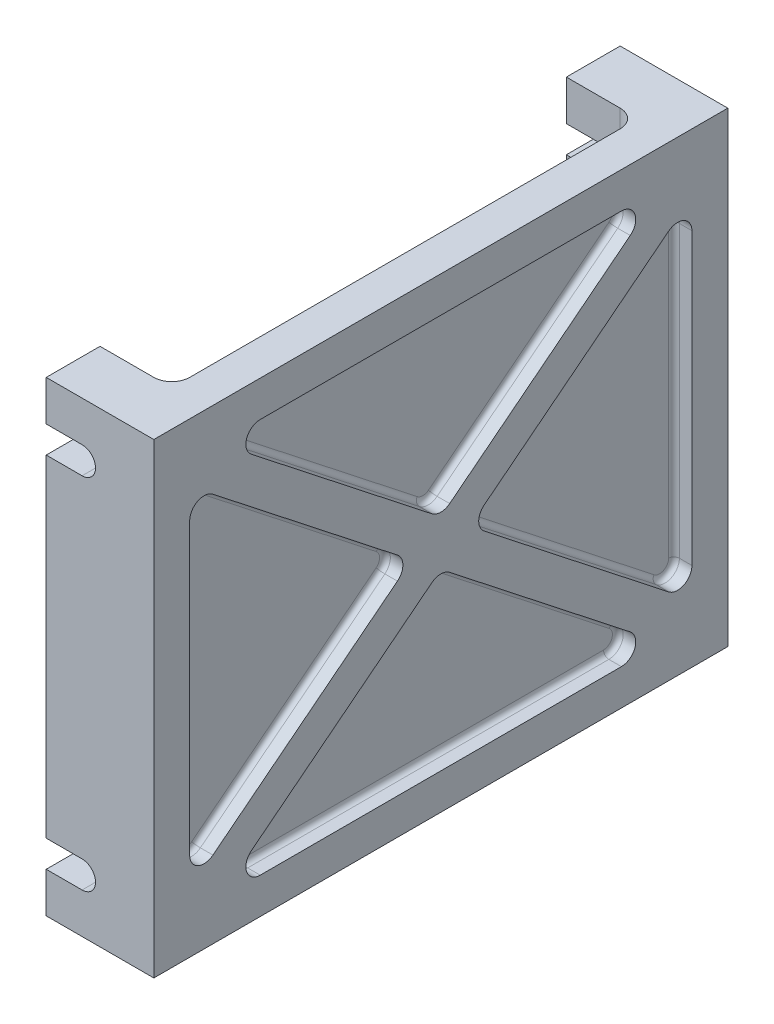
SolidWorks part; units mm, degrees
ref_plane "Front Plane" through (0, 0, 0) normal (0, 0, 1) x (1, 0, 0)
ref_plane "Top Plane" through (0, 0, 0) normal (0, 1, 0) x (1, 0, 0)
ref_plane "Right Plane" through (0, 0, 0) normal (1, 0, 0) x (0, 0, -1)
sketch "Sketch1" plane through (0, 0, 0) normal (1, 0, 0) x (0, 0, -1)
  line L1 (50.8, -41.275) -> (-50.8, -41.275)
  line L2 (50.8, -41.275) -> (50.8, 41.275)
  line L3 (50.8, 41.275) -> (-50.8, 41.275)
  line L4 (-50.8, -41.275) -> (-50.8, 41.275)
  line L5 (50.8, -41.275) -> (-50.8, 41.275) construction
  line L6 (50.8, 41.275) -> (-50.8, -41.275) construction
  point P0 (0, 0)
  dimension "D1" = 101.6
  dimension "D2" = 82.55
extrude "Boss-Extrude1" add sketch "Sketch1" along normal blind 3.175
sketch "Sketch2" plane through (3.175, 0, 0) normal (1, 0, 0) x (0, 0, -1)
  line L0 (50.8, 41.275) -> (-50.8, 41.275) construction
  line L1 (31.967, -34.925) -> (-31.967, -34.925)
  line L2 (44.45, -25.6612) -> (44.45, 25.6612)
  line L3 (31.967, 34.925) -> (-31.967, 34.925)
  line L4 (-44.45, -25.6612) -> (-44.45, 25.6612)
  line L5 (2.5695, -2.0189) -> (-2.5695, 2.0189) construction
  line L6 (2.5695, 2.0189) -> (-2.5695, -2.0189) construction
  line L7 (-50.8, 41.275) -> (-50.8, -41.275) construction
  line L8 (33.5363, -30.3878) -> (1.5693, -5.2708)
  line L9 (-33.5363, 30.3878) -> (-1.5693, 5.2708)
  line L10 (33.5363, 30.3878) -> (1.5693, 5.2708)
  line L11 (40.3407, 27.6585) -> (7.681, 1.9972)
  line L12 (-1.5693, -5.2708) -> (-33.5363, -30.3878)
  line L13 (-7.681, 1.9972) -> (-40.3407, 27.6585)
  line L14 (-7.681, -1.9972) -> (-40.3407, -27.6585)
  line L15 (7.681, -1.9972) -> (40.3407, -27.6585)
  line L17 (50.8, -41.275) -> (-50.8, -41.275)
  line L18 (50.8, -41.275) -> (50.8, 41.275)
  line L19 (50.8, 41.275) -> (-50.8, 41.275)
  line L20 (-50.8, -41.275) -> (-50.8, 41.275)
  line L21 (50.8, -41.275) -> (-50.8, 41.275) construction
  line L22 (50.8, 41.275) -> (-50.8, -41.275) construction
  arc A0 (-1.5693, -5.2708) -> (1.5693, -5.2708) centre (0, -7.268) cw
  arc A1 (7.681, -1.9972) -> (7.681, 1.9972) centre (9.2502, 0) cw
  arc A2 (1.5693, 5.2708) -> (-1.5693, 5.2708) centre (0, 7.268) cw
  arc A3 (-7.681, 1.9972) -> (-7.681, -1.9972) centre (-9.2502, 0) cw
  arc A4 (-40.3407, -27.6585) -> (-44.45, -25.6612) centre (-41.91, -25.6612) cw
  arc A5 (-33.5363, -30.3878) -> (-31.967, -34.925) centre (-31.967, -32.385) ccw
  arc A6 (33.5363, -30.3878) -> (31.967, -34.925) centre (31.967, -32.385) cw
  arc A7 (40.3407, -27.6585) -> (44.45, -25.6612) centre (41.91, -25.6612) ccw
  arc A8 (40.3407, 27.6585) -> (44.45, 25.6612) centre (41.91, 25.6612) cw
  arc A9 (33.5363, 30.3878) -> (31.967, 34.925) centre (31.967, 32.385) ccw
  arc A10 (-33.5363, 30.3878) -> (-31.967, 34.925) centre (-31.967, 32.385) cw
  arc A11 (-40.3407, 27.6585) -> (-44.45, 25.6612) centre (-41.91, 25.6612) ccw
  point P0 (0, 0)
  point P30 (-5.139, 0)
  point P47 (0, 0)
  line M9 (-50.8, 41.275) -> (-50.8, -41.275)
  line M10 (-50.8, -41.275) -> (50.8, -41.275)
  line M11 (50.8, -41.275) -> (50.8, 41.275)
  line M12 (50.8, 41.275) -> (-50.8, 41.275)
  dimension "D7" = 2.54
  dimension "D1" = 6.35
  dimension "D2" = 6.35
  dimension "D3" = 3.175
  dimension "D4" = 3.175
  dimension "D5" = 3.175
  dimension "D6" = 3.175
extrude "Boss-Extrude2" add sketch "Sketch2" along normal blind 3.175 contours A11 L13 A3 L14 A4 L4 L8 A6 L1 A5 L12 A0 L11 A8 L2 A7 L15 A1 L9 A10 L3 A9 L10 A2 M12 M9 M10 M11
fillet "Fillet1" radius 0.9525 24 edges at (3.175, -33.2152, -34.3675) (3.175, -34.925, 0) (3.175, -33.2152, 34.3675) (3.175, -17.8293, 17.5528) (3.175, -4.728, 0) (3.175, -17.8293, -17.5528) (3.175, 27.9457, -43.0203) (3.175, 0, -44.45) (3.175, -27.9457, -43.0203) (3.175, -14.8279, -24.0109) (3.175, 0, -6.7102) (3.175, 14.8279, -24.0109) (3.175, 33.2152, 34.3675) (3.175, 34.925, 0) (3.175, 33.2152, -34.3675) (3.175, 17.8293, -17.5528) (3.175, 4.728, 0) (3.175, 17.8293, 17.5528) (3.175, 14.8279, 24.0109) (3.175, 0, 6.7102) (3.175, -14.8279, 24.0109) (3.175, -27.9457, 43.0203) (3.175, 0, 44.45) (3.175, 27.9457, 43.0203)
sketch "Sketch3" plane through (0, 0, -50.8) normal (0, 0, -1) x (-1, 0, 0)
  line L0 (-6.35, -41.275) -> (0, -41.275) construction
  line L1 (0, 41.275) -> (12.7, 41.275)
  line L2 (0, 41.275) -> (0, -41.275)
  line L3 (0, -41.275) -> (12.7, -41.275)
  line L4 (12.7, 41.275) -> (12.7, -41.275)
  dimension "D1" = 0
  dimension "D2" = 12.7
extrude "Boss-Extrude3" add sketch "Sketch3" against normal blind 9.525
sketch "Sketch4" plane through (0, 0, 50.8) normal (0, 0, 1) x (1, 0, 0)
  line L1 (0, 41.275) -> (-12.7, 41.275)
  line L2 (0, 41.275) -> (0, -41.275)
  line L3 (0, -41.275) -> (-12.7, -41.275)
  line L4 (-12.7, 41.275) -> (-12.7, -41.275)
extrude "Boss-Extrude4" add sketch "Sketch4" against normal blind 9.525
fillet "Fillet2" radius 3.175 2 edges at (0, 0, 41.275)
sketch "Sketch5" plane through (0, 0, 50.8) normal (0, 0, 1) x (1, 0, 0)
  line L0 (6.35, -41.275) -> (-12.7, -41.275) construction
  line L1 (6.35, 41.275) -> (-12.7, 41.275) construction
  line L2 (-12.7, 41.275) -> (-12.7, -41.275) construction
  line L3 (-6.35, 34.1312) -> (-12.7, 34.1312)
  line L4 (-12.7, 34.1312) -> (-12.7, 29.3687)
  line L5 (-12.7, 29.3687) -> (-6.35, 29.3687)
  line L6 (-6.35, -29.3688) -> (-12.7, -29.3688)
  line L7 (-12.7, -29.3688) -> (-12.7, -34.1313)
  line L8 (-12.7, -34.1313) -> (-6.35, -34.1313)
  circle A0 centre (-6.35, 31.75) radius 2.3812
  circle A1 centre (-6.35, -31.75) radius 2.3813
  line M2 (-12.7, 41.275) -> (-12.7, -41.275)
  dimension "D1" = 4.7625
  dimension "D2" = 9.525
  dimension "D3" = 9.525
  dimension "D4" = 6.35
  dimension "D5" = 6.35
  dimension "D6" = 4.7625
extrude "Cut-Extrude2" cut sketch "Sketch5" against normal through all contours A0 L3 L5 M2 | A1 | A1 L6 L8 M2
